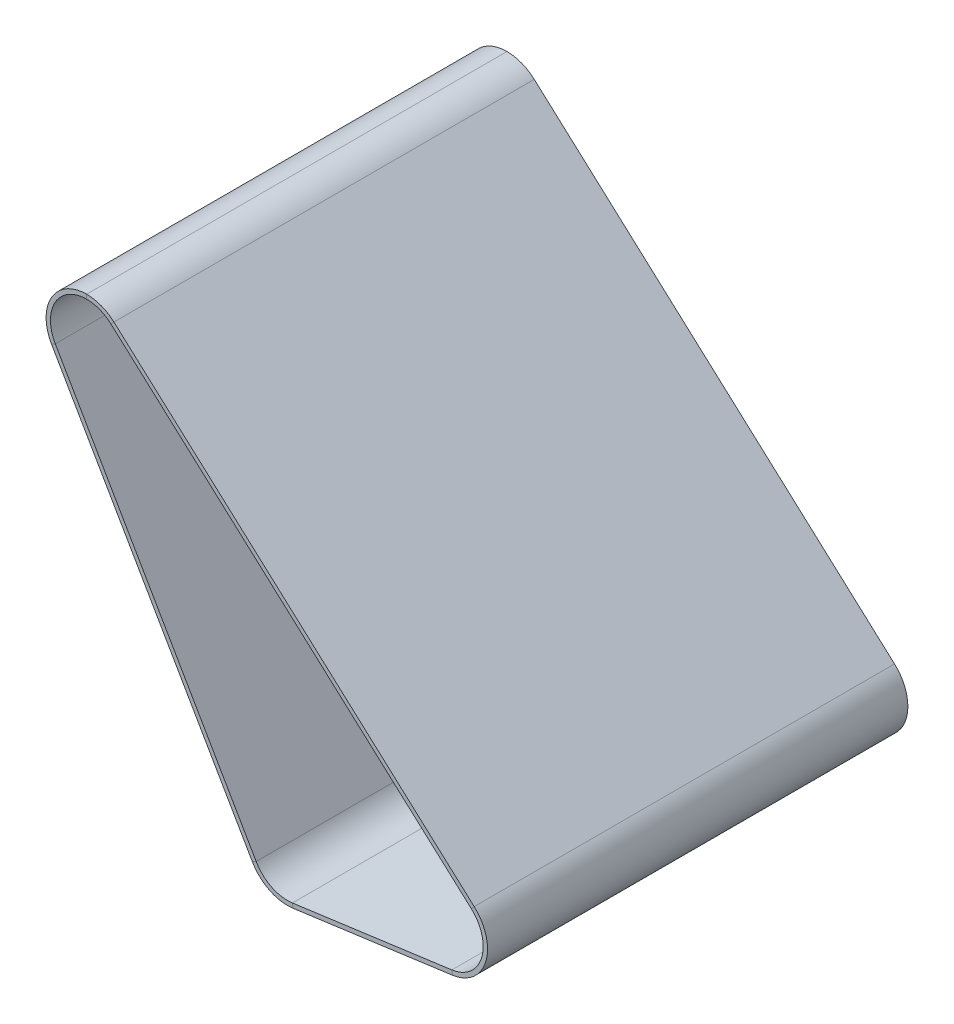
SolidWorks part; units mm, degrees
ref_plane "Plan de face" through (0, 0, 0) normal (0, 0, 1) x (1, 0, 0)
ref_plane "Plan de dessus" through (0, 0, 0) normal (0, 1, 0) x (1, 0, 0)
ref_plane "Plan de droite" through (0, 0, 0) normal (1, 0, 0) x (0, 0, -1)
sketch "Esquisse2" plane through (0, 0, 0) normal (0, 0, 1) x (1, 0, 0)
  line L0 (0, 0) -> (1, 0) construction
  line L1 (0, 0) -> (0, 1) construction
  line L2 (-21.6506, -12.5) -> (116.9134, -252.5)
  line L3 (141.9419, -264.7708) -> (251.9419, -249.7708)
  line L4 (265.3414, -206.4656) -> (16.7773, 18.5344)
  arc A0 (16.7773, 18.5344) -> (-21.6506, -12.5) centre (0, 0) ccw
  arc A1 (116.9134, -252.5) -> (141.9419, -264.7708) centre (138.5641, -240) ccw
  arc A2 (251.9419, -249.7708) -> (265.3414, -206.4656) centre (248.5641, -225) ccw
sketch "Esquisse3" plane through (0, 0, 0) normal (1, 0, 0) x (0, 0, -1)
  line L0 (-145, 25) -> (145, 25) construction
  line L1 (-145, 28) -> (145, 28)
  line L2 (-145, 28) -> (-145, 25)
  line L3 (-145, 25) -> (145, 25)
  line L4 (145, 28) -> (145, 25)
  line L6 (0, 25) -> (0, 0) construction
  line L8 (0, 25) -> (0, -12.5) construction
  line L9 (0, 25) -> (0, -12.5) construction
  point P7 (0, 25)
  dimension "D1" = 290
  dimension "D2" = 3
sweep "Balayage1" add profiles "Esquisse3" path "Esquisse2"
